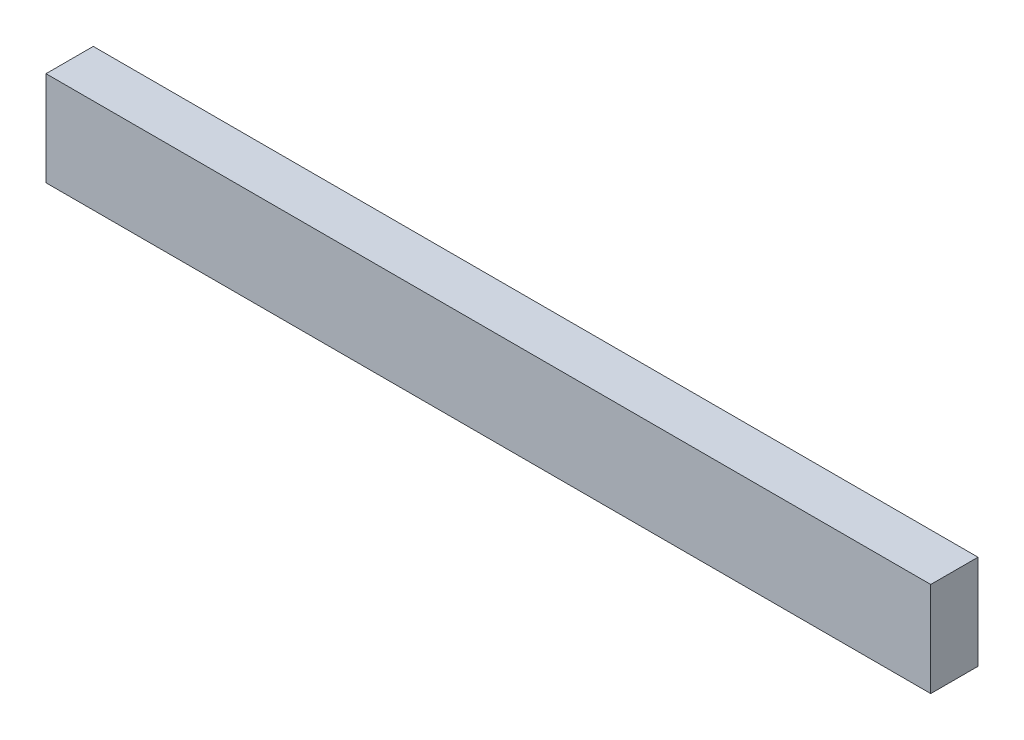
SolidWorks part; units mm, degrees
ref_plane "Plan de face" through (0, 0, 0) normal (0, 0, 1) x (1, 0, 0)
ref_plane "Plan de dessus" through (0, 0, 0) normal (0, 1, 0) x (1, 0, 0)
ref_plane "Plan de droite" through (0, 0, 0) normal (1, 0, 0) x (0, 0, -1)
sketch "Esquisse1" plane through (0, 0, 0) normal (0, 0, 1) x (1, 0, 0)
  line L1 (0, 0) -> (468, 0)
  line L2 (0, 0) -> (0, 50)
  line L3 (0, 50) -> (468, 50)
  line L4 (468, 0) -> (468, 50)
  dimension "D1" = 50
  dimension "D2" = 468
extrude "Boss.-Extru.1" add sketch "Esquisse1" along normal blind 25
